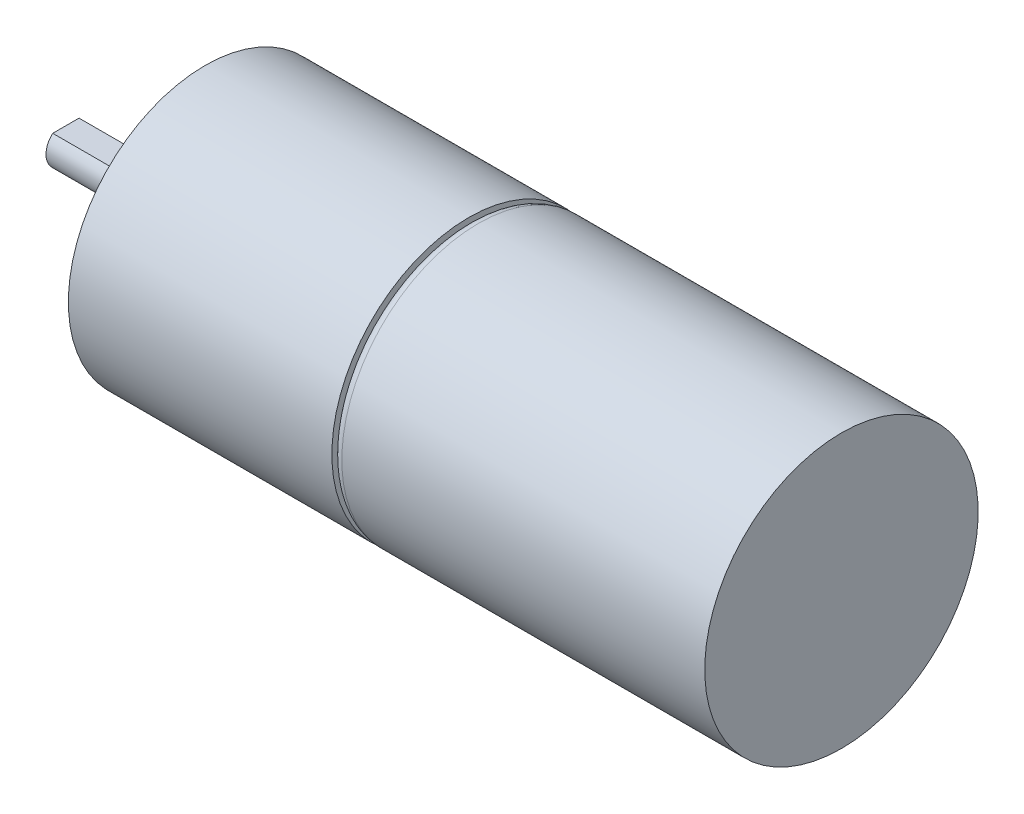
SolidWorks part; units mm, degrees
ref_plane "Front Plane" through (0, 0, 0) normal (0, 0, 1) x (1, 0, 0)
ref_plane "Top Plane" through (0, 0, 0) normal (0, 1, 0) x (1, 0, 0)
ref_plane "Right Plane" through (0, 0, 0) normal (1, 0, 0) x (0, 0, -1)
sketch "Sketch1" plane through (0, 0, 0) normal (0, 0, 1) x (1, 0, 0)
  line L0 (0, 0) -> (0, 2)
  line L1 (0, 2) -> (12, 2)
  line L2 (12, 2) -> (12, 3.5)
  line L3 (12, 3.5) -> (14, 3.5)
  line L4 (14, 3.5) -> (14, 13.75)
  line L5 (14, 13.75) -> (40.5, 13.75)
  line L7 (78, 13.75) -> (78, 0)
  line L8 (78, 0) -> (0, 0)
  line L11 (78, 13.75) -> (41.5, 13.75)
  line L12 (40.5, 13.75) -> (40.5, 12.75)
  arc A0 (40.5, 12.75) -> (41.5, 13.75) centre (41.5, 12.75) cw
  dimension "D8" = 1
  dimension "D1" = 2
  dimension "D2" = 12
  dimension "D3" = 1.5
  dimension "D4" = 2
  dimension "D5" = 13.75
  dimension "D6" = 26.5
  dimension "D7" = 37.5
revolve "Revolve1" add sketch "Sketch1" angle 360 about L8
sketch "Sketch2" plane through (14, 0, 0) normal (-1, 0, 0) x (0, 0, 1)
  line L0 (-13.75, 0) -> (13.75, 0) construction
  circle A0 centre (0, 0) radius 13.75 construction
  point P4 (10, 0)
  point P5 (-10, 0)
  dimension "D1" = 10
  dimension "D2" = 10
hole_wizard "M3 Tapped Hole1" positions "3DSketch1" profile "Sketch3" tap size "M3" standard "ISO"
sketch3d "3DSketch1"
  point P0 (14, 0, -10)
  point P3 (14, 0, 10)
sketch "Sketch3" plane through (14, 0, -10) normal (0, 1, 0) x (0, 0, 1)
  line L0 (0, 0) -> (0, 2.7511)
  line L1 (0, 2.7511) -> (1.25, 2)
  line L2 (1.25, 2) -> (1.25, 0)
  line L5 (1.25, 0) -> (0, 0)
  line L10 (0, 2.7511) -> (-1.25, 2) construction
  line L11 (0, -6.35) -> (0, 107.95) construction
  dimension "Tap Drill Dia." = 2.5
  dimension "Tap Drill Depth" = 2
  dimension "Drill Angle" = 118
cosmetic thread "Hole Thread1" parameters "D1"=2, "D2"=3
cosmetic thread "Hole Thread2" parameters "D1"=2, "D2"=3
sketch "Sketch4" plane through (0, 0, 0) normal (-1, 0, 0) x (0, 0, 1)
  line L0 (-1.3229, 1.5) -> (1.3229, 1.5)
  circle A0 centre (0, 0) radius 2 construction
  circle A1 centre (0, 0) radius 2 construction
  arc A2 (-1.3229, 1.5) -> (1.3229, 1.5) centre (0, 0) cw
  dimension "D1" = 1.5
extrude "Cut-Extrude1" cut sketch "Sketch4" against normal blind 10
